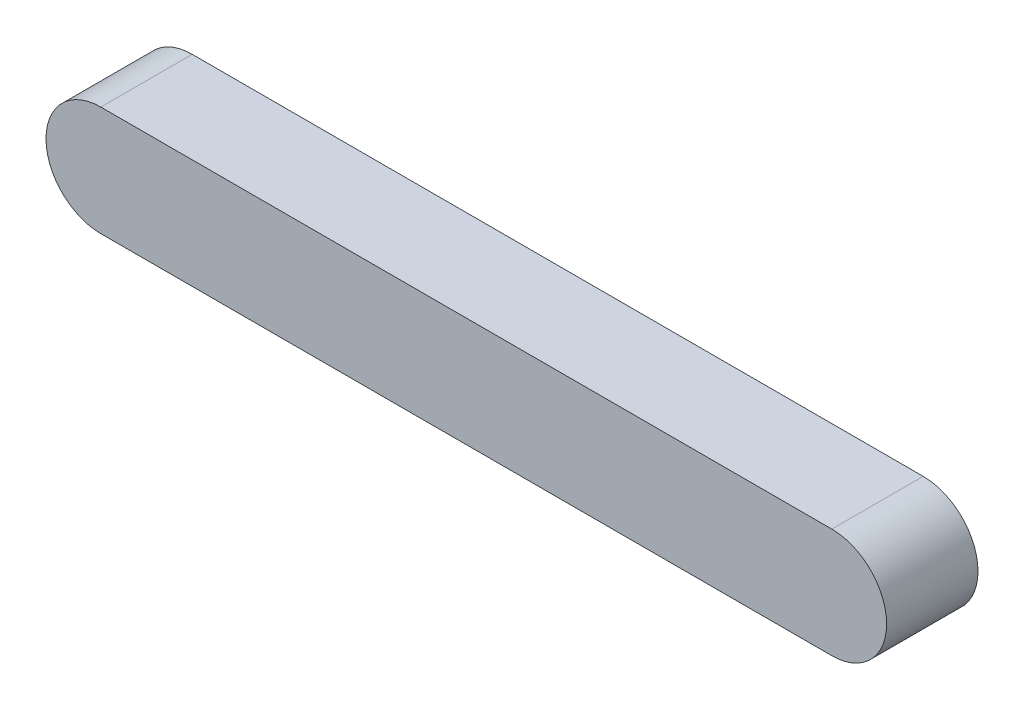
SolidWorks part; units mm, degrees
ref_plane "Front Plane" through (0, 0, 0) normal (0, 0, 1) x (1, 0, 0)
ref_plane "Top Plane" through (0, 0, 0) normal (0, 1, 0) x (1, 0, 0)
ref_plane "Right Plane" through (0, 0, 0) normal (1, 0, 0) x (0, 0, -1)
sketch "Sketch1" plane through (0, 0, 0) normal (0, 0, 1) x (1, 0, 0)
  line L0 (0, 0) -> (40, 0) construction
  line L1 (0, 3) -> (40, 3)
  line L2 (0, -3) -> (40, -3)
  arc A0 (0, 3) -> (0, -3) centre (0, 0) ccw
  arc A1 (40, -3) -> (40, 3) centre (40, 0) ccw
  point P3 (20, 0)
  dimension "D1" = 40
  dimension "D2" = 6
extrude "Boss-Extrude1" add sketch "Sketch1" along normal blind 5
